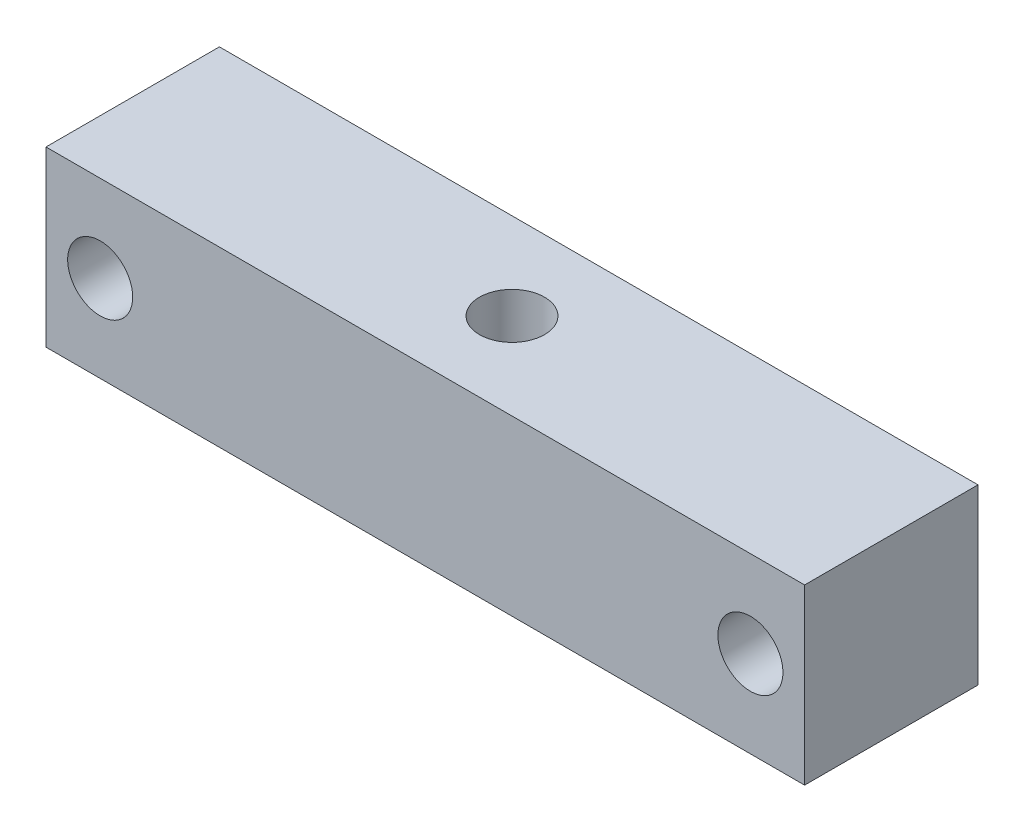
SolidWorks part; units mm, degrees
ref_plane "前视基准面" through (0, 0, 0) normal (0, 0, 1) x (1, 0, 0)
ref_plane "上视基准面" through (0, 0, 0) normal (0, 1, 0) x (1, 0, 0)
ref_plane "右视基准面" through (0, 0, 0) normal (1, 0, 0) x (0, 0, -1)
sketch "草图1" plane through (0, 0, 0) normal (0, 0, 1) x (1, 0, 0)
  line L1 (-17.5, 4) -> (17.5, 4)
  line L2 (-17.5, 4) -> (-17.5, -4)
  line L3 (-17.5, -4) -> (17.5, -4)
  line L4 (17.5, 4) -> (17.5, -4)
  line L5 (-17.5, 4) -> (17.5, -4) construction
  line L6 (-17.5, -4) -> (17.5, 4) construction
  point P0 (0, 0)
  dimension "D1" = 35
  dimension "D2" = 8
extrude "凸台-拉伸2" add sketch "草图1" along normal blind 8
sketch "草图3" plane through (0, 0, 0) normal (0, 0, -1) x (-1, 0, 0)
  line L0 (-15, 0) -> (15, 0) construction
  line L1 (0, 4.4) -> (0, -4.4) construction
  circle A0 centre (-15, 0) radius 1.5
  circle A1 centre (15, 0) radius 1.5
  point P4 (0, 0)
  dimension "D2" = 3
  dimension "D1" = 30
extrude "切除-拉伸1" cut sketch "草图3" against normal blind 8
cosmetic thread "装饰螺纹线4" parameters "D1"=5, "D2"=4
cosmetic thread "装饰螺纹线6" parameters "D1"=5, "D2"=4
sketch "草图4" plane through (0, 4, 0) normal (0, 1, 0) x (1, 0, 0)
  line L0 (0, 0) -> (0, -4) construction
  circle A0 centre (0, -4) radius 1.5
  dimension "D2" = 3
  dimension "D1" = 4
extrude "切除-拉伸2" cut sketch "草图4" against normal blind 8
cosmetic thread "装饰螺纹线5" parameters "D1"=5, "D2"=4
